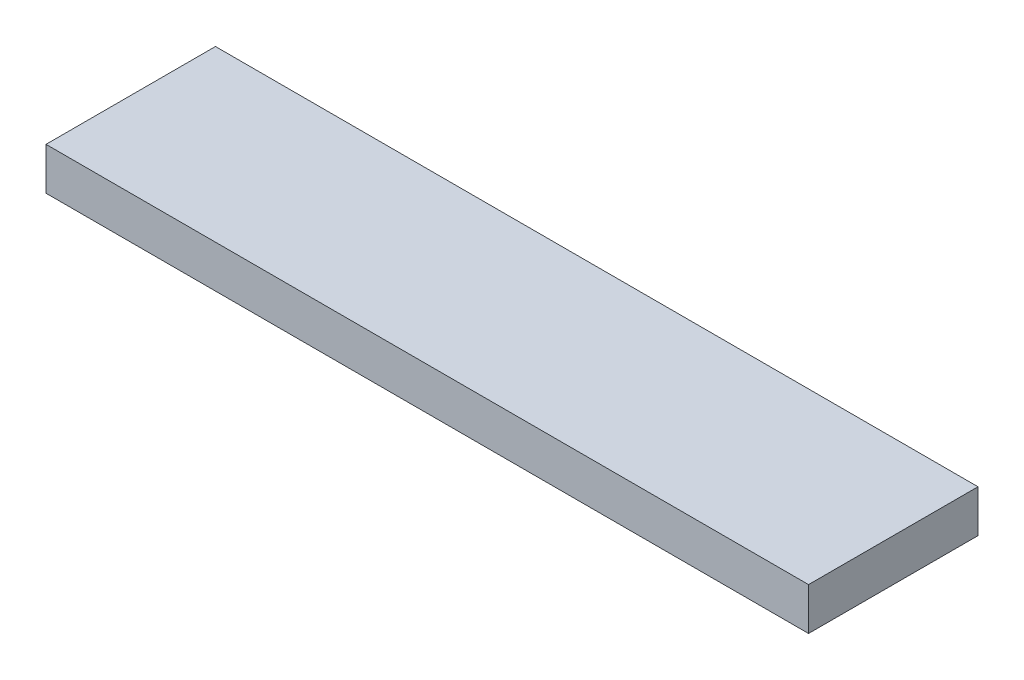
SolidWorks part; units mm, degrees
ref_plane "前视基准面" through (0, 0, 0) normal (0, 0, 1) x (1, 0, 0)
ref_plane "上视基准面" through (0, 0, 0) normal (0, 1, 0) x (1, 0, 0)
ref_plane "右视基准面" through (0, 0, 0) normal (1, 0, 0) x (0, 0, -1)
sketch "草图1" plane through (0, 0, 0) normal (0, 1, 0) x (1, 0, 0)
  line L1 (0, 0) -> (18, 0)
  line L2 (0, 0) -> (0, 4)
  line L3 (0, 4) -> (18, 4)
  line L4 (18, 0) -> (18, 4)
  dimension "D1" = 18
  dimension "D2" = 4
extrude "凸台-拉伸1" add sketch "草图1" along normal blind 1
